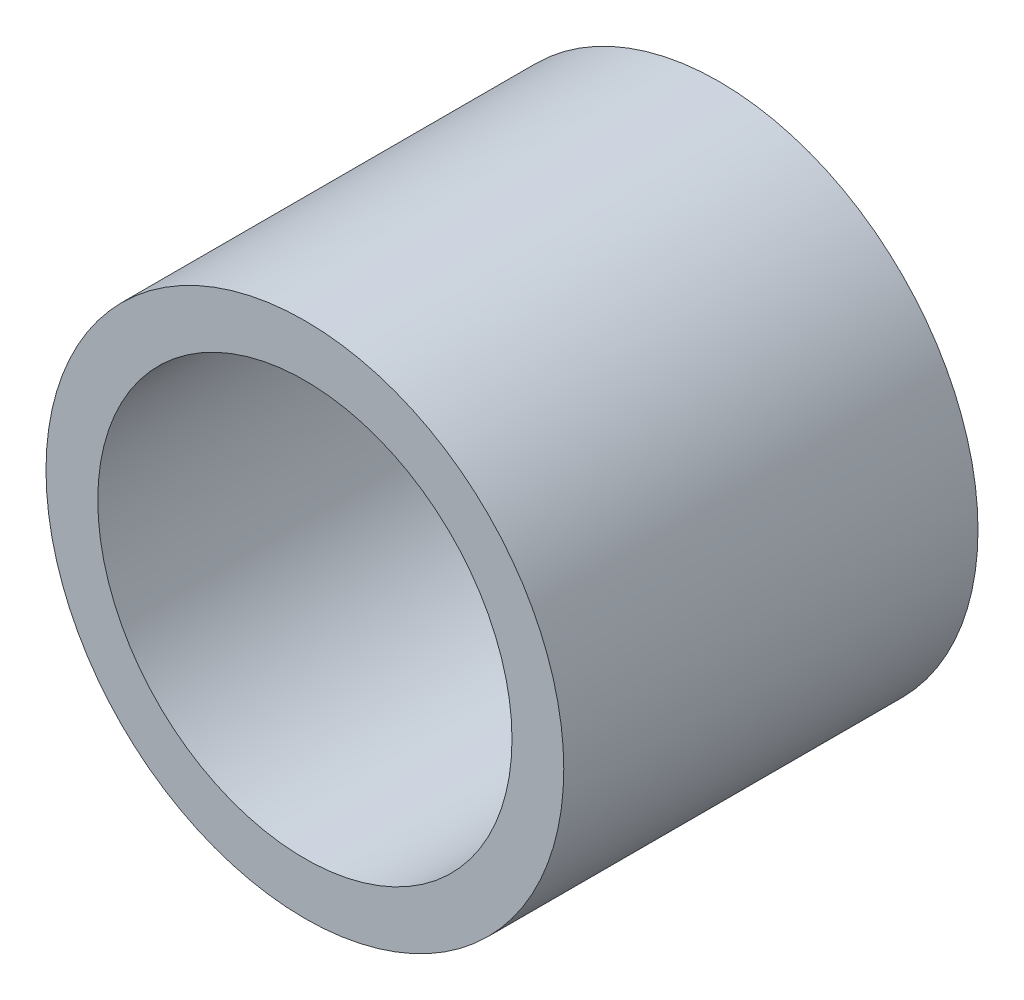
SolidWorks part; units mm, degrees
ref_plane "Plan de face" through (0, 0, 0) normal (0, 0, 1) x (1, 0, 0)
ref_plane "Plan de dessus" through (0, 0, 0) normal (0, 1, 0) x (1, 0, 0)
ref_plane "Plan de droite" through (0, 0, 0) normal (1, 0, 0) x (0, 0, -1)
sketch "Esquisse1" plane through (0, 0, 0) normal (0, 0, 1) x (1, 0, 0)
  circle A0 centre (0, 63.6714) radius 7.5 construction
  circle A1 centre (0, 63.6714) radius 7.5
  circle A2 centre (0, 63.6714) radius 6
  dimension "D1" = 12
extrude "Extrusion1" add sketch "Esquisse1" along normal blind 12
